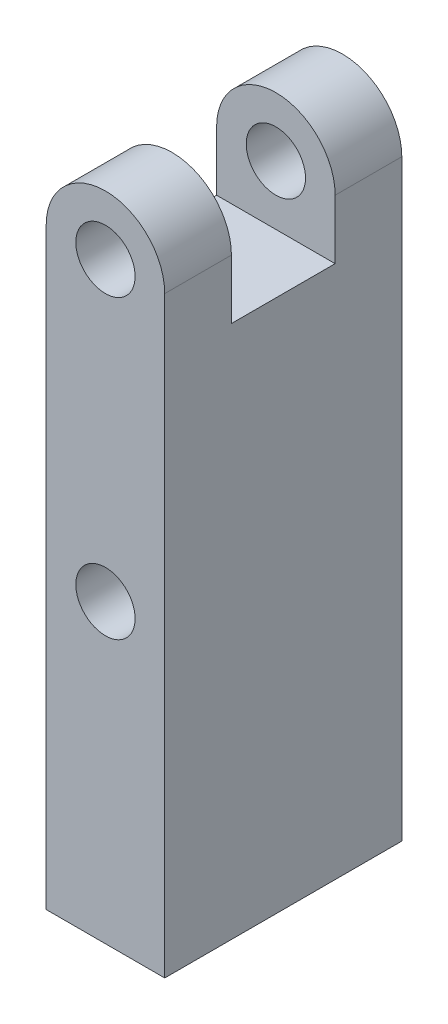
SolidWorks part; units mm, degrees
ref_plane "前视基准面" through (0, 0, 0) normal (0, 0, 1) x (1, 0, 0)
ref_plane "上视基准面" through (0, 0, 0) normal (0, 1, 0) x (1, 0, 0)
ref_plane "右视基准面" through (0, 0, 0) normal (1, 0, 0) x (0, 0, -1)
sketch "草图1" plane through (0, 0, 0) normal (0, 0, 1) x (1, 0, 0)
  line L0 (-0.2443, 7.1324) -> (-0.2443, -6.3098) construction
  line L2 (-1.2443, -4.5637) -> (-1.2443, 5.4363)
  line L4 (0.7557, -4.5637) -> (0.7557, 5.4363)
  line L5 (0.7557, -4.5637) -> (-1.2443, -4.5637)
  arc A0 (0.7557, 5.4363) -> (-1.2443, 5.4363) centre (-0.2443, 5.4363) ccw
  circle A2 centre (-0.2443, 5.4363) radius 0.5
  circle A4 centre (-0.2443, 0.4363) radius 0.5
  point P0 (0, 0)
  dimension "D2" = 1
  dimension "D3" = 1
  dimension "D6" = 1
  dimension "D5" = 10
  dimension "D7" = 5
extrude "凸台-拉伸1" add sketch "草图1" along normal blind 4
sketch "草图4" plane through (0, 0, 0) normal (1, 0, 0) x (0, 0, -1)
  line L0 (-2, 6.4363) -> (-2, -6.8439) construction
  line L1 (0, 6.4363) -> (-4, 6.4363) construction
  line L2 (-2.875, 6.4363) -> (-2.875, 4.4363)
  line L3 (-2.875, 4.4363) -> (-1.125, 4.4363)
  line L4 (-1.125, 4.4363) -> (-1.125, 6.4363)
  dimension "D1" = 1.75
  dimension "D2" = 2
extrude "切除-拉伸1" cut sketch "草图4" against normal through all and the other way through all
